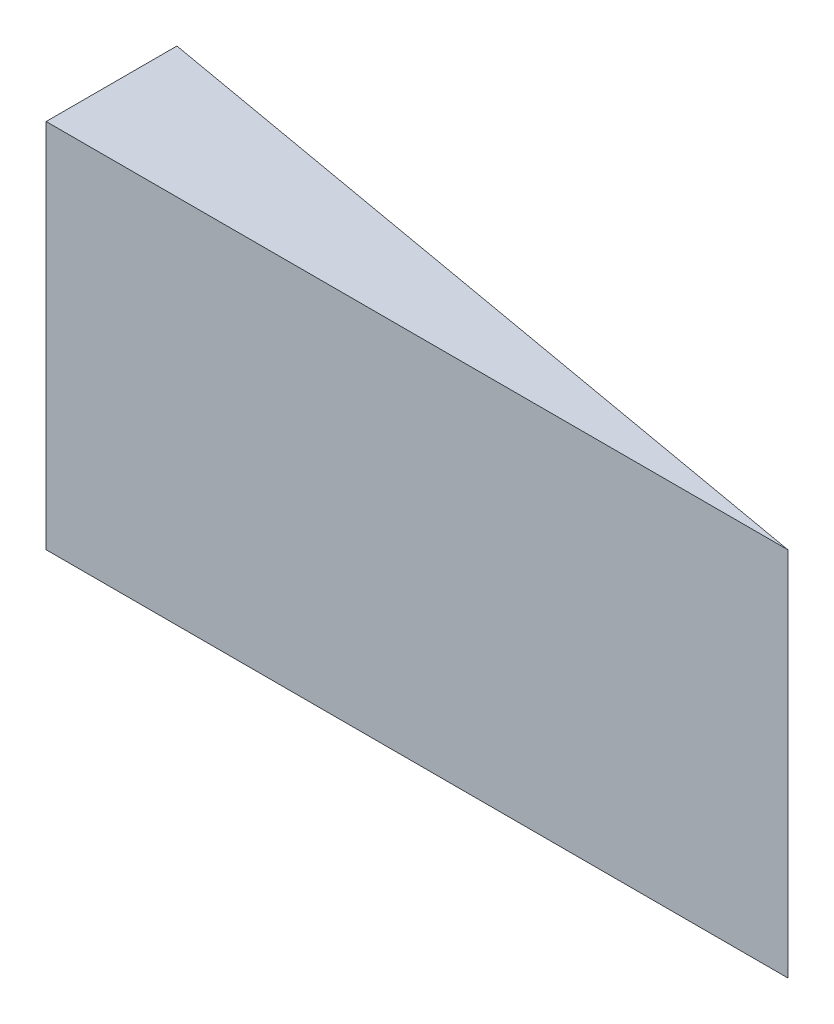
SolidWorks part; units mm, degrees
ref_plane "Přední rovina" through (0, 0, 0) normal (0, 0, 1) x (1, 0, 0)
ref_plane "Horní rovina" through (0, 0, 0) normal (0, 1, 0) x (1, 0, 0)
ref_plane "Pravá rovina" through (0, 0, 0) normal (1, 0, 0) x (0, 0, -1)
sketch "Sketch1" plane through (0, 0, 0) normal (0, 1, 0) x (1, 0, 0)
  line L0 (0, 0) -> (40, 0)
  line L1 (40, 0) -> (0, 7.0531)
  line L2 (0, 7.0531) -> (0, 0)
  point P4 (0, 0)
  point P5 (0, 0)
  point P6 (0, 16.8591)
  dimension "D1" = 10
  dimension "D2" = 40
extrude "Boss-Extrude1" add sketch "Sketch1" along normal blind 20
